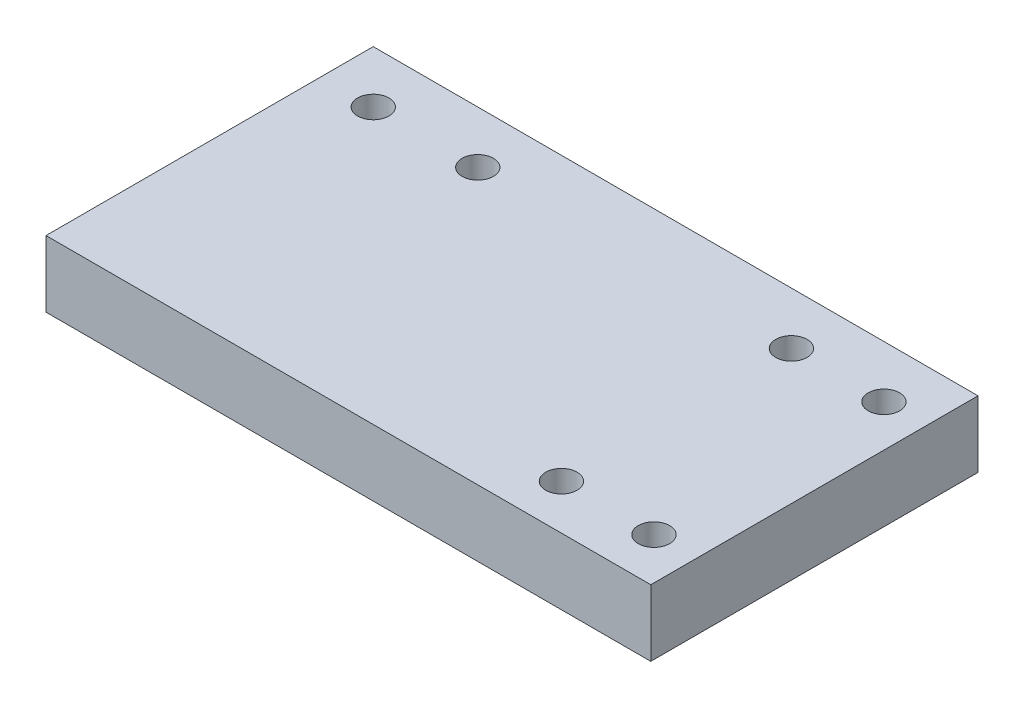
SolidWorks part; units mm, degrees
ref_plane "Front Plane" through (0, 0, 0) normal (0, 0, 1) x (1, 0, 0)
ref_plane "Top Plane" through (0, 0, 0) normal (0, 1, 0) x (1, 0, 0)
ref_plane "Right Plane" through (0, 0, 0) normal (1, 0, 0) x (0, 0, -1)
sketch "Sketch1" plane through (0, 0, 0) normal (0, 1, 0) x (1, 0, 0)
  line L0 (10, 31.3) -> (10, 18.5952) construction
  line L1 (0, 0) -> (49.85, 0)
  line L2 (0, 0) -> (0, 31.3)
  line L3 (0, 31.3) -> (49.85, 31.3)
  line L6 (49.85, 31.3) -> (57.85, 31.3)
  line L8 (49.85, 0) -> (57.85, 0)
  line L9 (57.85, 31.3) -> (57.85, 0)
  circle A0 centre (45, 26.3) radius 1.5
  circle A1 centre (45, 4.3) radius 1.5
  circle A2 centre (15, 26.3) radius 1.5
  circle A3 centre (5, 26.3) radius 1.5
  circle A4 centre (53.85, 26.3) radius 1.5
  circle A5 centre (53.85, 4.3) radius 1.5
  dimension "D5" = 3
  dimension "D9" = 3
  dimension "D13" = 3
  dimension "D1" = 31.3
  dimension "D2" = 49.85
  dimension "D3" = 22
  dimension "D4" = 30
  dimension "D7" = 5
  dimension "D8" = 5
  dimension "D10" = 5
  dimension "D11" = 5
  dimension "D12" = 8
  dimension "D14" = 4
  dimension "D15" = 5
  dimension "D6" = 12.85
  dimension "D16" = 10
extrude "Boss-Extrude1" add sketch "Sketch1" along normal blind 6.35
equation "\"D2@Sketch1\"=36.85+13"
